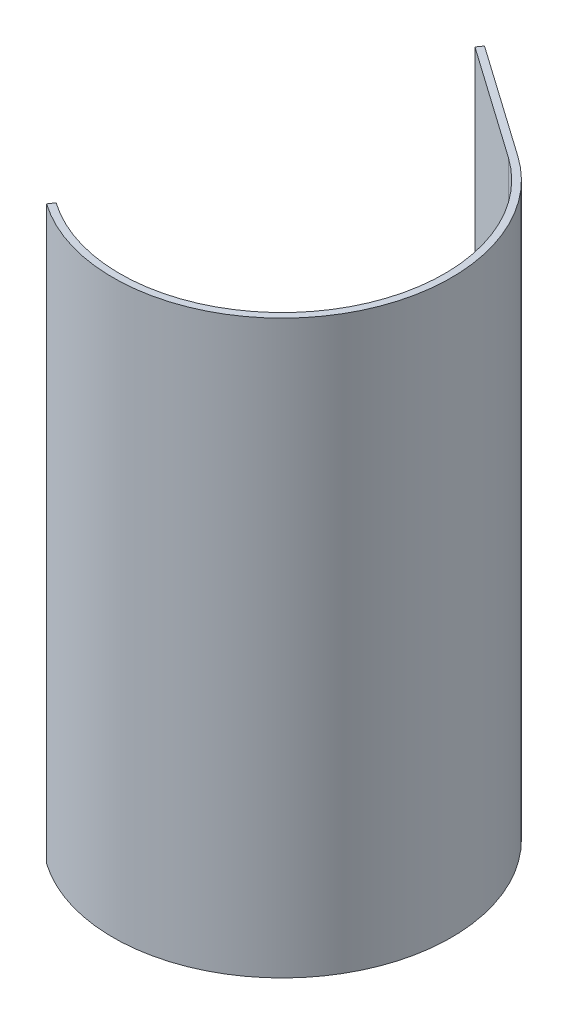
SolidWorks part; units mm, degrees
ref_plane "Plan de face" through (0, 0, 0) normal (0, 0, 1) x (1, 0, 0)
ref_plane "Plan de dessus" through (0, 0, 0) normal (0, 1, 0) x (1, 0, 0)
ref_plane "Plan de droite" through (0, 0, 0) normal (1, 0, 0) x (0, 0, -1)
sketch "Esquisse1" plane through (0, 0, 0) normal (0, 1, 0) x (1, 0, 0)
  line L0 (42.5453, 60.5466) -> (-42.5453, -60.5466)
  circle A0 centre (0, 0) radius 74
  circle A1 centre (0, 0) radius 71
  dimension "D1" = 148
  dimension "D3" = 3
  dimension "D2" = 148
extrude "Boss.-Extru.1" add sketch "Esquisse1" along normal blind 250 contours L0 A0
sketch "Esquisse7" plane through (0, 0, 0) normal (-0.8182, 0, -0.5749) x (-0.5749, 0, 0.8182)
  line L0 (-71, 250) -> (-71, 0) construction
  line L1 (-74, 0) -> (-71, 0)
  line L2 (-74, 0) -> (-74, 250)
  line L3 (-74, 250) -> (-71, 250)
  line L4 (-71, 0) -> (-71, 250)
  line L5 (74, 250) -> (74, 0) construction
  line L6 (71, 0) -> (74, 0)
  line L7 (71, 0) -> (71, 250)
  line L8 (71, 250) -> (74, 250)
  line L9 (74, 0) -> (74, 250)
  line L10 (-74, 250) -> (-71, 250) construction
  line L11 (71, 250) -> (74, 250) construction
  line M1 (-74, 0) -> (-71, 0)
  line M2 (-71, 0) -> (-71, 250)
  line M3 (-71, 250) -> (-74, 250)
  line M4 (-74, 250) -> (-74, 0)
extrude "Boss.-Extru.4" add sketch "Esquisse7" along normal blind 60 contours M4 M1 M2 M3
